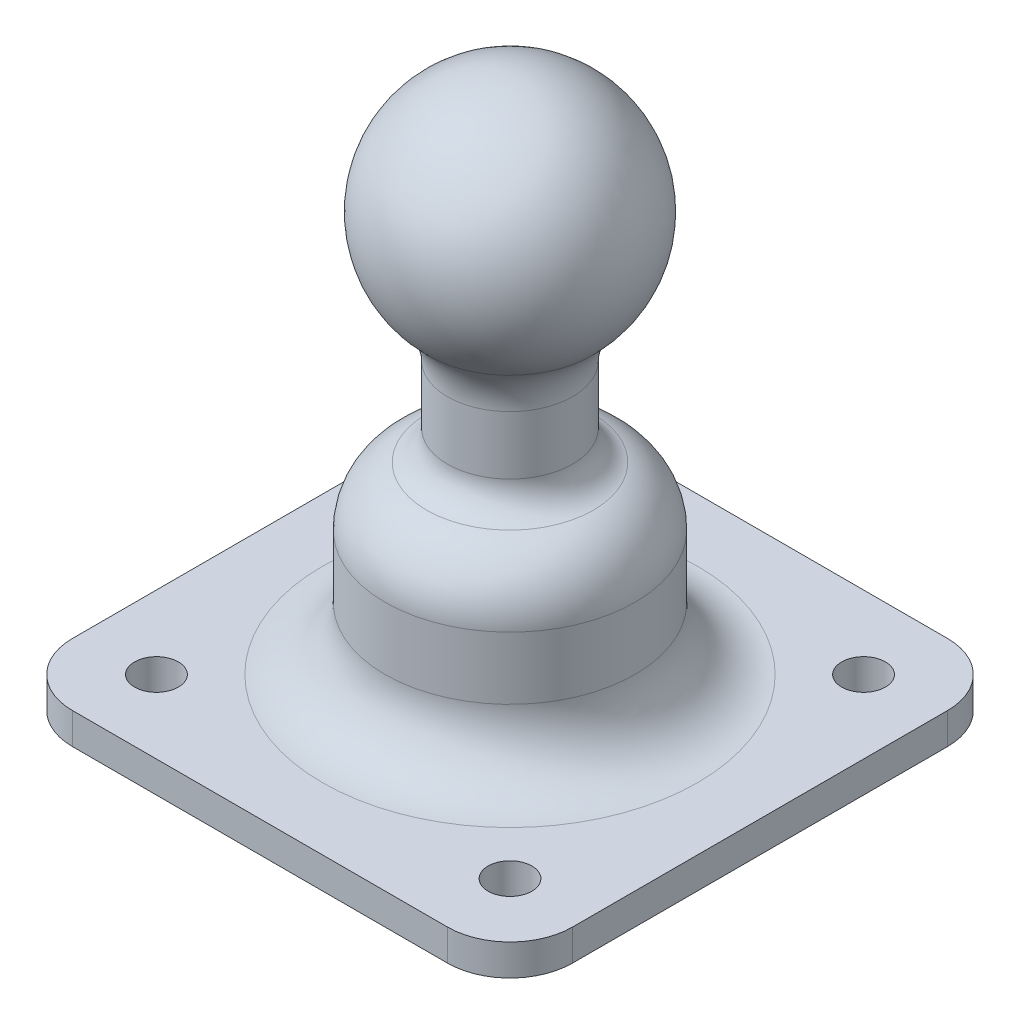
SolidWorks part; units mm, degrees
material "ABS"
ref_plane "Front Plane" through (0, 0, 0) normal (0, 0, 1) x (1, 0, 0)
ref_plane "Top Plane" through (0, 0, 0) normal (0, 1, 0) x (1, 0, 0)
ref_plane "Right Plane" through (0, 0, 0) normal (1, 0, 0) x (0, 0, -1)
sketch "Sketch1" plane through (0, 0, 0) normal (0, 1, 0) x (1, 0, 0)
  line L1 (-30, 40) -> (30, 40)
  line L2 (-40, 30) -> (-40, -30)
  line L3 (-30, -40) -> (30, -40)
  line L4 (40, 30) -> (40, -30)
  line L5 (-40, 40) -> (40, -40) construction
  line L6 (-40, -40) -> (40, 40) construction
  circle A0 centre (0, 0) radius 40 construction
  circle A1 centre (-28.2843, 28.2843) radius 3.5
  circle A2 centre (28.2843, 28.2843) radius 3.5
  circle A3 centre (28.2843, -28.2843) radius 3.5
  circle A4 centre (-28.2843, -28.2843) radius 3.5
  arc A5 (-40, -30) -> (-30, -40) centre (-30, -30) ccw
  arc A6 (30, -40) -> (40, -30) centre (30, -30) ccw
  arc A7 (30, 40) -> (40, 30) centre (30, 30) cw
  arc A8 (-30, 40) -> (-40, 30) centre (-30, 30) ccw
  point P0 (0, 0)
  dimension "D2" = 7
  dimension "D3" = 10
  dimension "D1" = 80
extrude "Boss-Extrude1" add sketch "Sketch1" along normal blind 5
sketch "Sketch2" plane through (0, 5, 0) normal (0, 1, 0) x (1, 0, 0)
  circle A0 centre (0, 0) radius 20
  dimension "D1" = 40
extrude "Boss-Extrude2" add sketch "Sketch2" along normal blind 30
fillet "Fillet1" radius 10 2 edges at (0, 5, 20) (0, 35, 20)
sketch "Sketch3" plane through (0, 35, 0) normal (0, 1, 0) x (1, 0, 0)
  circle A0 centre (0, 0) radius 10
  dimension "D1" = 20
extrude "Boss-Extrude3" add sketch "Sketch3" along normal blind 20
fillet "Fillet2" radius 5 1 edges at (0, 35, 10)
sketch "Sketch4" plane through (0, 0, 0) normal (0, 0, 1) x (1, 0, 0)
  line L0 (0, 55) -> (0, 69.1421) construction
  line L1 (10, 55) -> (-10, 55) construction
  line L2 (0, 50.3921) -> (0, 87.8921)
  line L3 (10, 39.1421) -> (-10, 39.1421) construction
  arc A0 (0, 50.3921) -> (0, 87.8921) centre (0, 69.1421) ccw
  arc A1 (0, 87.8921) -> (0, 50.3921) centre (0, 69.1421) ccw construction
  dimension "D1" = 18.75
  dimension "D2" = 30
revolve "Revolve1" add sketch "Sketch4" angle 360 about L0
fillet "Fillet3" radius 10 1 edges at (0, 53.2814, 10)
